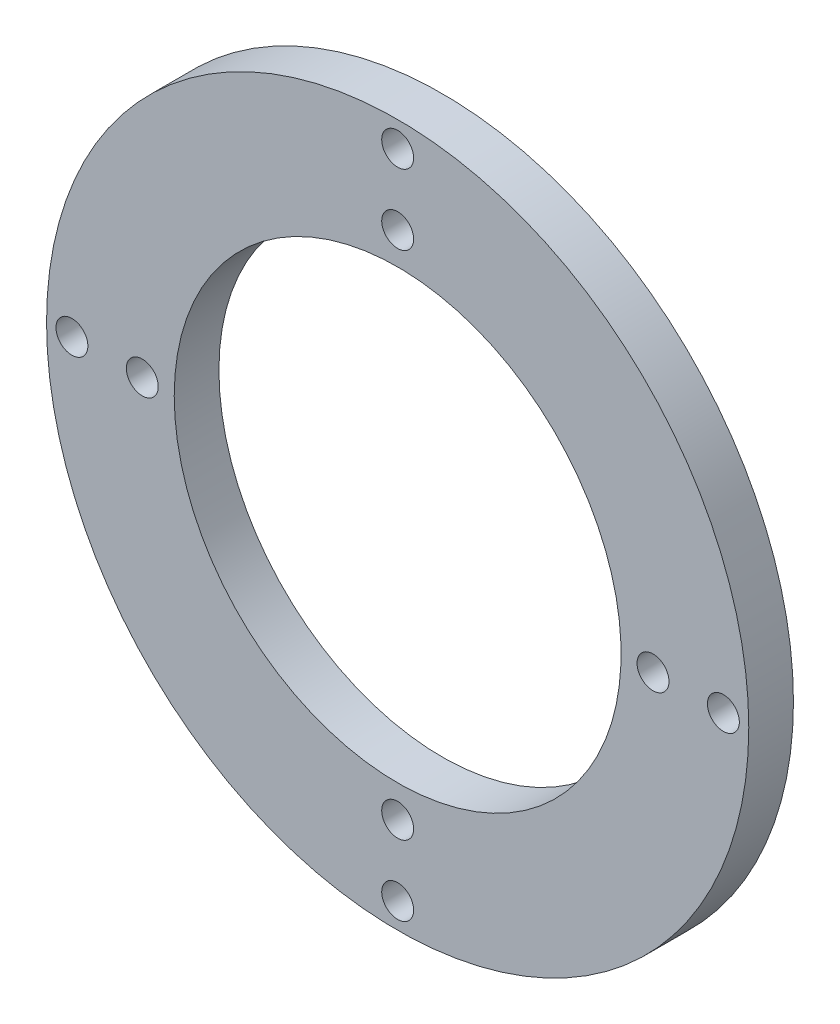
SolidWorks part; units mm, degrees
ref_plane "Front Plane" through (0, 0, 0) normal (0, 0, 1) x (1, 0, 0)
ref_plane "Top Plane" through (0, 0, 0) normal (0, 1, 0) x (1, 0, 0)
ref_plane "Right Plane" through (0, 0, 0) normal (1, 0, 0) x (0, 0, -1)
sketch "Sketch1" plane through (0, 0, 0) normal (0, 0, 1) x (1, 0, 0)
  line L0 (0, 45) -> (0, 35) construction
  circle A0 centre (0, 0) radius 35
  circle A1 centre (0, 0) radius 45
  circle A2 centre (0, 40) radius 2.5
  circle A3 centre (40, 0) radius 2.5
  circle A4 centre (0, -40) radius 2.5
  circle A5 centre (-40, 0) radius 2.5
  point P9 (0, 40)
  point P18 (0, 0)
  dimension "D1" = 70
  dimension "D2" = 10
  dimension "D3" = 5
  dimension "D4" = 4
extrude "Boss-Extrude1" add sketch "Sketch1" along normal blind 7
sketch "Sketch2" plane through (0, 0, 7) normal (0, 0, 1) x (1, 0, 0)
  circle A0 centre (0, 0) radius 55
  circle A1 centre (0, 0) radius 45
  circle A2 centre (0, 0) radius 47.0473
  dimension "D1" = 10
extrude "Boss-Extrude3" add sketch "Sketch2" against normal blind 7 separate body contours A0 A2
sketch "Sketch3" plane through (0, 0, 7) normal (0, 0, 1) x (1, 0, 0)
  circle A0 centre (0, 0) radius 47.0473
  circle A1 centre (0, 0) radius 45
extrude "Boss-Extrude4" add sketch "Sketch3" against normal blind 4
sketch "Sketch4" plane through (0, 0, 0) normal (0, 0, -1) x (-1, 0, 0)
  line L0 (0, -40) -> (0, -55) construction
  line L1 (0, -55) -> (0, -47.0473) construction
  circle A0 centre (0, 0) radius 55 construction
  circle A1 centre (0, -51.0236) radius 2.5
  circle A2 centre (-51.0236, 0) radius 2.5
  circle A3 centre (0, 51.0236) radius 2.5
  circle A4 centre (51.0236, 0) radius 2.5
  point P18 (0, 0)
  dimension "D1" = 5
  dimension "D2" = 4
extrude "Cut-Extrude1" cut sketch "Sketch4" against normal through all
